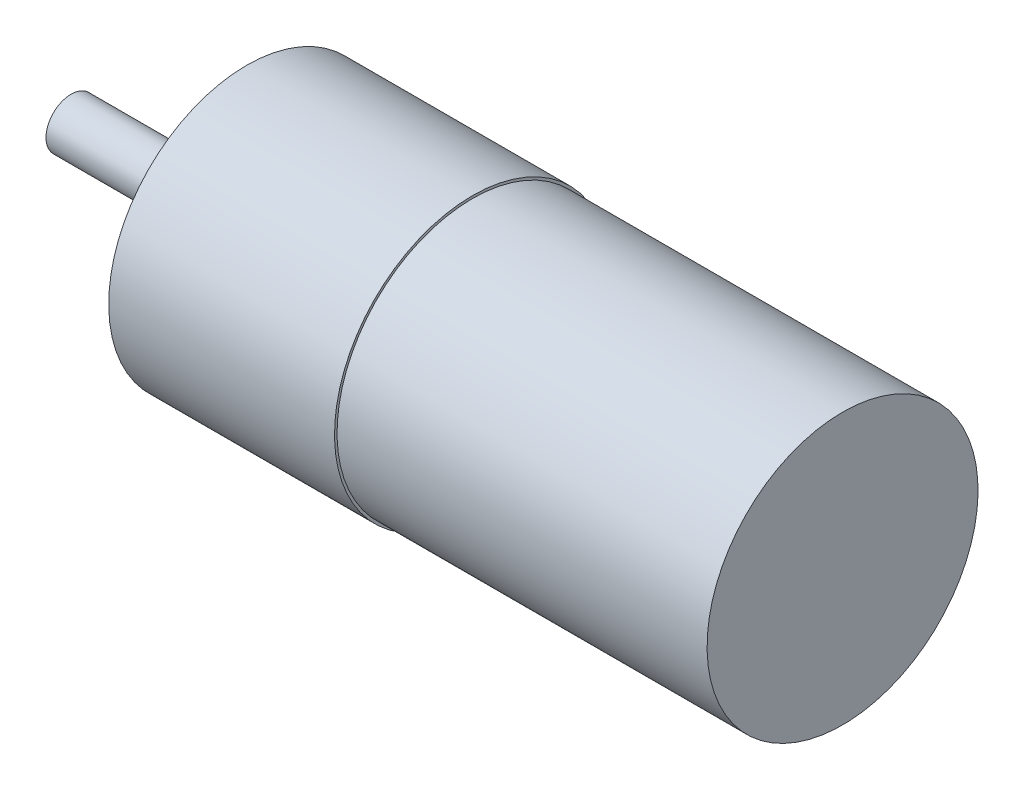
SolidWorks part; units mm, degrees
material "7075-T6 (SN)"
ref_plane "Front Plane" through (0, 0, 0) normal (0, 0, 1) x (1, 0, 0)
ref_plane "Top Plane" through (0, 0, 0) normal (0, 1, 0) x (1, 0, 0)
ref_plane "Right Plane" through (0, 0, 0) normal (1, 0, 0) x (0, 0, -1)
sketch "Sketch2" plane through (0, 0, 0) normal (0, 0, 1) x (1, 0, 0)
  line L1 (0, 0) -> (29.5, 0)
  line L2 (0, 0) -> (0, -10.8)
  line L3 (0, -10.8) -> (29.5, -10.8)
  line L4 (29.5, 0) -> (29.5, -10.8)
  line L5 (0, 0) -> (-18, 0)
  line L6 (0, 0) -> (0, -11)
  line L7 (0, -11) -> (-18, -11)
  line L8 (-18, 0) -> (-18, -11)
  line L9 (-18, 0) -> (-20, 0)
  line L10 (-18, 0) -> (-18, -7)
  line L11 (-18, -7) -> (-20, -7)
  line L12 (-20, 0) -> (-20, -7)
  line L13 (-20, 0) -> (-32, 0)
  line L14 (-20, 0) -> (-20, -2)
  line L15 (-20, -2) -> (-32, -2)
  line L16 (-32, 0) -> (-32, -2)
  dimension "D1" = 10.8
  dimension "D2" = 29.5
  dimension "D3" = 18
  dimension "D4" = 11
  dimension "D5" = 2
  dimension "D6" = 12
  dimension "D7" = 2
revolve "Revolve1" add sketch "Sketch2" angle 360 about L5
hole_wizard "Ø2.0mm Dowel Hole1" positions "Sketch4" profile "Sketch6" hole size "Ø2.0" standard "ISO"
sketch "Sketch4" plane through (-18, 0, 0) normal (-1, 0, 0) x (0, 0, 1)
  circle A0 centre (0, 0) radius 9
  point P0 (-9, 0)
  point P2 (0, 9)
  point P4 (9, 0)
  point P6 (0, -9)
  point P11 (0, 0)
  point P12 (0, 0)
  point P13 (0, 0)
  point P14 (0, 0)
  point P15 (0, 0)
  point P16 (0, 0)
sketch "Sketch6" plane through (-18, 0, -9) normal (0, 1, 0) x (0, 0, 1)
  line L0 (0, 0) -> (0, 1.0009)
  line L1 (0, 1.0009) -> (1, 0.4)
  line L2 (1, 0.4) -> (1, 0)
  line L5 (1, 0) -> (0, 0)
  line L10 (0, 1.0009) -> (-1, 0.4) construction
  line L11 (0, -6.35) -> (0, 107.95) construction
  dimension "Hole Dia." = 2
  dimension "Hole Depth" = 0.4
  dimension "Drill Angle" = 118
